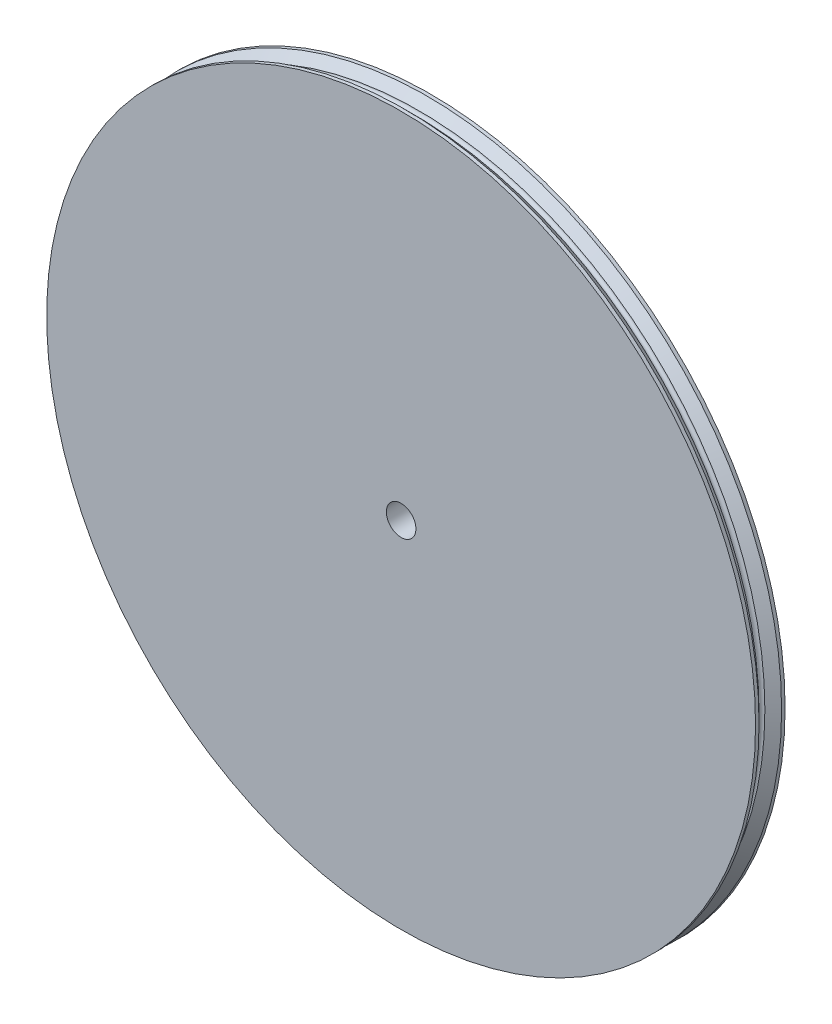
SolidWorks part; units mm, degrees
ref_plane "Front Plane" through (0, 0, 0) normal (0, 0, 1) x (1, 0, 0)
ref_plane "Top Plane" through (0, 0, 0) normal (0, 1, 0) x (1, 0, 0)
ref_plane "Right Plane" through (0, 0, 0) normal (1, 0, 0) x (0, 0, -1)
sketch "Sketch1" plane through (0, 0, 0) normal (0, 1, 0) x (1, 0, 0)
  line L0 (6.35, 6.35) -> (152.4, 6.35)
  line L1 (152.4, 6.35) -> (152.4, 4.85)
  line L2 (152.4, 4.85) -> (148.8, 1.25)
  line L3 (148.8, -1.25) -> (152.4, -4.85)
  line L4 (152.4, -4.85) -> (152.4, -6.35)
  line L5 (152.4, -6.35) -> (6.35, -6.35)
  line L6 (6.35, -6.35) -> (6.35, 6.35)
  line L7 (0, -6.35) -> (0, 6.35) construction
  arc A0 (148.8, 1.25) -> (148.8, -1.25) centre (148.8, 0) ccw
  point P13 (6.35, 0)
  dimension "D2" = 1.25
  dimension "D1" = 304.8
  dimension "D3" = 1.5
  dimension "D4" = 12.7
  dimension "D5" = 12.7
revolve "Revolve1" add sketch "Sketch1" angle 360 about L7
